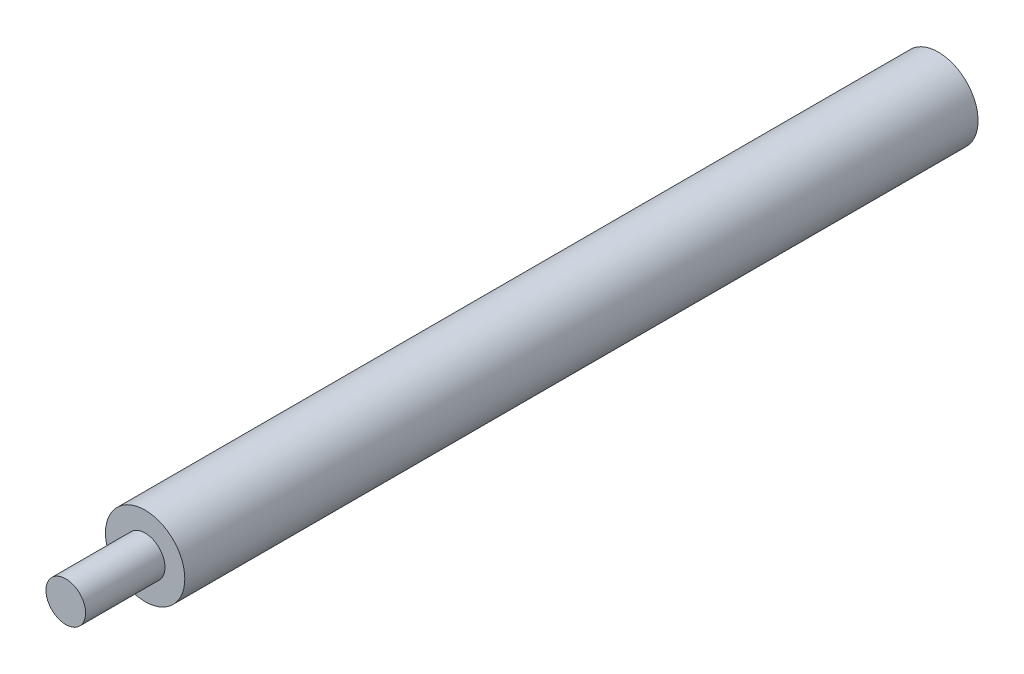
SolidWorks part; units mm, degrees
ref_plane "Front Plane" through (0, 0, 0) normal (0, 0, 1) x (1, 0, 0)
ref_plane "Top Plane" through (0, 0, 0) normal (0, 1, 0) x (1, 0, 0)
ref_plane "Right Plane" through (0, 0, 0) normal (1, 0, 0) x (0, 0, -1)
sketch "Sketch1" plane through (0, 0, 0) normal (0, 0, 1) x (1, 0, 0)
  circle A1 centre (0, 0) radius 2.5
  dimension "D2" = 5
extrude "Boss-Extrude1" add sketch "Sketch1" along normal blind 60
sketch "Sketch2" plane through (0, 0, 60) normal (0, 0, 1) x (1, 0, 0)
  circle A0 centre (0, 0) radius 1.25
  dimension "D1" = 2.5
extrude "Boss-Extrude2" add sketch "Sketch2" along normal blind 5
sketch "Sketch3" plane through (0, 0, 0) normal (0, 0, -1) x (-1, 0, 0)
  circle A0 centre (0, 0) radius 1.25
  dimension "D1" = 2.5
extrude "Cut-Extrude1" cut sketch "Sketch3" against normal blind 5
sketch "Sketch4" plane through (0, 0, 0) normal (0, 0, -1) x (-1, 0, 0)
  circle A0 centre (0, 0) radius 2.6198
extrude "Cut-Extrude2" cut sketch "Sketch4" against normal blind 10
sketch "Sketch5" plane through (0, 0, 10) normal (0, 0, -1) x (-1, 0, 0)
  circle A0 centre (0, 0) radius 1.25
  dimension "D1" = 2.5
extrude "Cut-Extrude3" cut sketch "Sketch5" against normal blind 5
